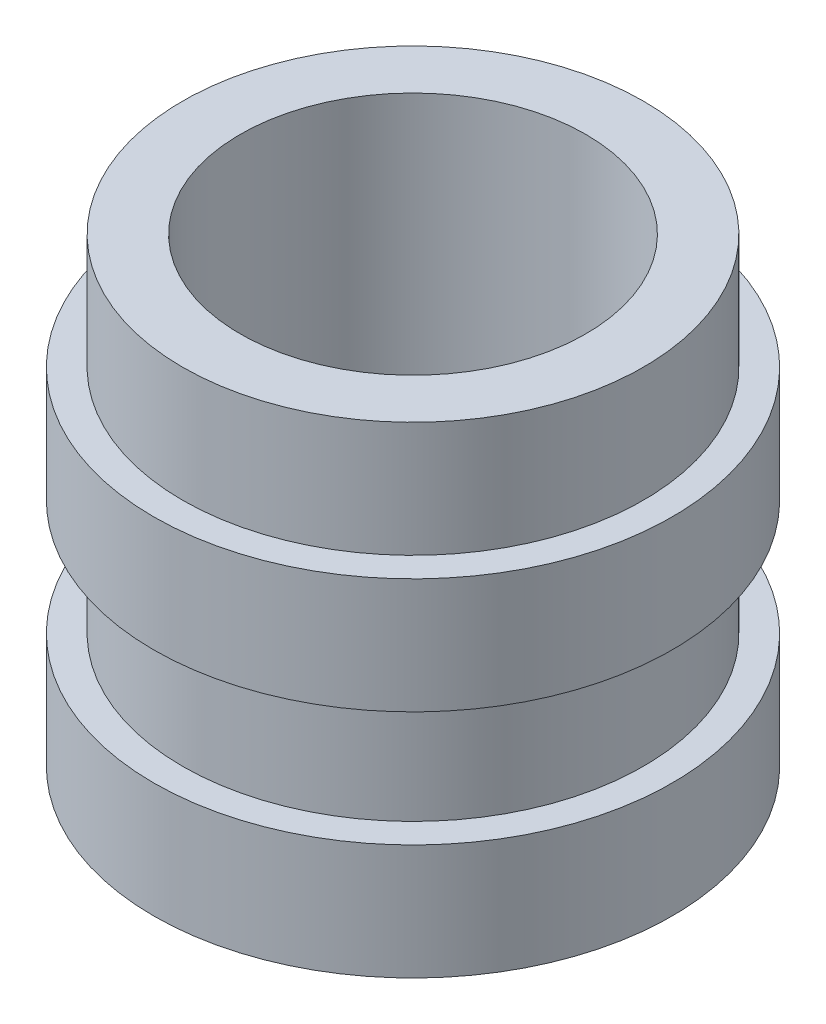
SolidWorks part; units mm, degrees
ref_plane "Front Plane" through (0, 0, 0) normal (0, 0, 1) x (1, 0, 0)
ref_plane "Top Plane" through (0, 0, 0) normal (0, 1, 0) x (1, 0, 0)
ref_plane "Right Plane" through (0, 0, 0) normal (1, 0, 0) x (0, 0, -1)
sketch "Sketch1" plane through (0, 0, 0) normal (0, 1, 0) x (1, 0, 0)
  circle A0 centre (0, 0) radius 2
  dimension "D1" = 4
extrude "Boss-Extrude1" add sketch "Sketch1" along normal blind 1
sketch "Sketch2" plane through (0, 0, 0) normal (0, -1, 0) x (1, 0, 0)
  circle A0 centre (0, 0) radius 2.25
  dimension "D1" = 4.5
extrude "Boss-Extrude2" add sketch "Sketch2" along normal blind 1
sketch "Sketch3" plane through (0, -1, 0) normal (0, -1, 0) x (1, 0, 0)
  circle A0 centre (0, 0) radius 2
  circle A1 centre (0, 0) radius 2 construction
extrude "Boss-Extrude3" add sketch "Sketch3" along normal blind 1
sketch "Sketch4" plane through (0, -2, 0) normal (0, -1, 0) x (1, 0, 0)
  circle A0 centre (0, 0) radius 2.25
  circle A1 centre (0, 0) radius 2.25 construction
extrude "Boss-Extrude4" add sketch "Sketch4" along normal blind 1
sketch "Sketch5" plane through (0, -3, 0) normal (0, -1, 0) x (1, 0, 0)
  circle A0 centre (0, 0) radius 1.5
  dimension "D1" = 3
extrude "Cut-Extrude1" cut sketch "Sketch5" against normal through all
